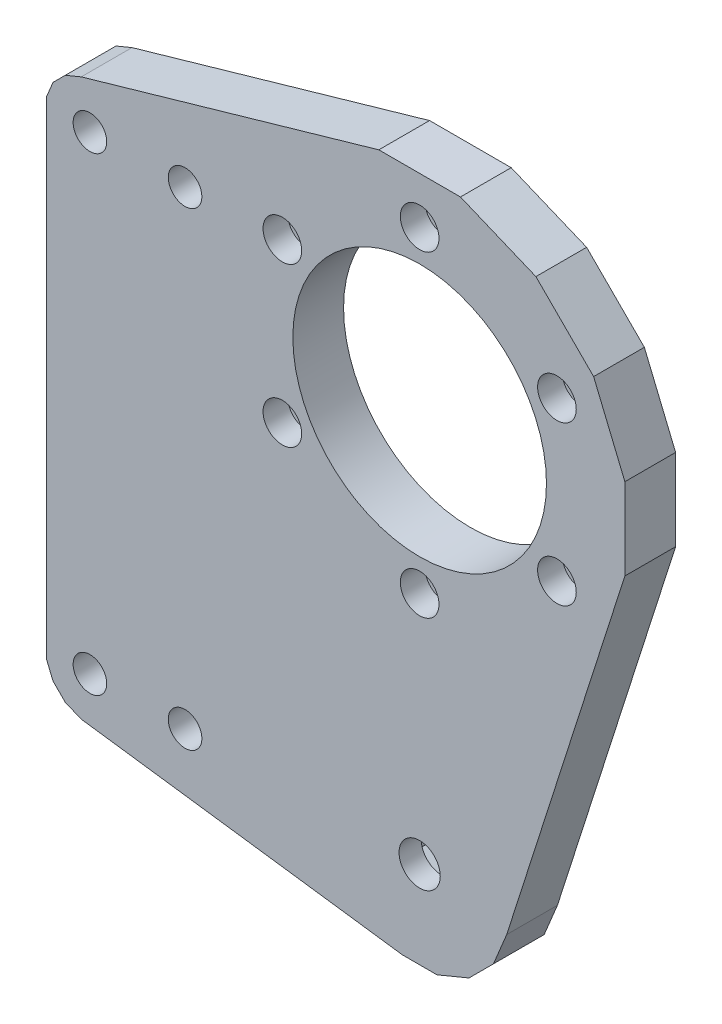
SolidWorks part; units mm, degrees
ref_plane "前视基准面" through (0, 0, 0) normal (0, 0, 1) x (1, 0, 0)
ref_plane "上视基准面" through (0, 0, 0) normal (0, 1, 0) x (1, 0, 0)
ref_plane "右视基准面" through (0, 0, 0) normal (1, 0, 0) x (0, 0, -1)
other "Configuration Table"
sketch "Profile_1" plane through (0, 0, 0) normal (0, 0, 1) x (1, 0, 0)
  line L0 (-58.8655, 13.3656) -> (-58.8655, -63.3656)
  line L1 (-58.8655, -63.3656) -> (-57.8203, -65.889)
  line L2 (-57.8203, -65.889) -> (-55.889, -67.8203)
  line L3 (-55.889, -67.8203) -> (-53.3656, -68.8655)
  line L4 (-53.3656, -68.8655) -> (-2.7313, -75.731)
  line L5 (-2.7313, -75.731) -> (2.7313, -75.731)
  line L6 (2.7313, -75.731) -> (7.778, -73.6406)
  line L7 (7.778, -73.6406) -> (11.6406, -69.778)
  line L8 (11.6406, -69.778) -> (13.731, -64.7313)
  line L9 (13.731, -64.7313) -> (32.3659, -6.438)
  line L10 (32.3659, -6.438) -> (32.3659, 6.438)
  line L11 (32.3659, 6.438) -> (27.4385, 18.3338)
  line L12 (27.4385, 18.3338) -> (18.3338, 27.4385)
  line L13 (18.3338, 27.4385) -> (6.438, 32.3659)
  line L14 (6.438, 32.3659) -> (-6.438, 32.3659)
  line L15 (-6.438, 32.3659) -> (-53.3656, 18.8655)
  line L16 (-53.3656, 18.8655) -> (-55.889, 17.8203)
  line L17 (-55.889, 17.8203) -> (-57.8203, 15.889)
  line L18 (-57.8203, 15.889) -> (-58.8655, 13.3656)
  circle A0 centre (0, 0) radius 20
  circle A1 centre (0, -62) radius 3.25
  circle A2 centre (21.6506, 12.5) radius 1.65
  circle A3 centre (0, 25) radius 1.65
  circle A4 centre (-21.6506, 12.5) radius 1.65
  circle A5 centre (-21.6506, -12.5) radius 1.65
  circle A6 centre (0, -25) radius 1.65
  circle A7 centre (21.6506, -12.5) radius 1.65
  circle A8 centre (-52, 12) radius 2.65
  circle A9 centre (-37, 12) radius 2.65
  circle A10 centre (-52, -62) radius 2.65
  circle A11 centre (-37, -62) radius 2.65
extrude "Frame_and_bench_interface" add sketch "Profile_1" along normal blind 8 from offset 1
sketch "Profile_2" plane through (0, 0, 0) normal (0, 0, 1) x (1, 0, 0)
  circle A0 centre (21.6506, 12.5) radius 3.05
  circle A1 centre (0, 25) radius 3.05
  circle A2 centre (-21.6506, 12.5) radius 3.05
  circle A3 centre (-21.6506, -12.5) radius 3.05
  circle A4 centre (0, -25) radius 3.05
  circle A5 centre (21.6506, -12.5) radius 3.05
extrude "Recess_stator_screw_heads" cut sketch "Profile_2" along normal blind 4 from offset 3.1
sketch "Profile_3" plane through (0, 0, 0) normal (0, 0, 1) x (1, 0, 0)
  line L0 (5.175, -59.0122) -> (0, -56.0244)
  line L1 (0, -56.0244) -> (-5.175, -59.0122)
  line L2 (-5.175, -59.0122) -> (-5.175, -64.9878)
  line L3 (-5.175, -64.9878) -> (0, -67.9756)
  line L4 (0, -67.9756) -> (5.175, -64.9878)
  line L5 (5.175, -64.9878) -> (5.175, -59.0122)
extrude "Rear_captive_nut_B" cut sketch "Profile_3" along normal blind 4.51 from offset 1.01
